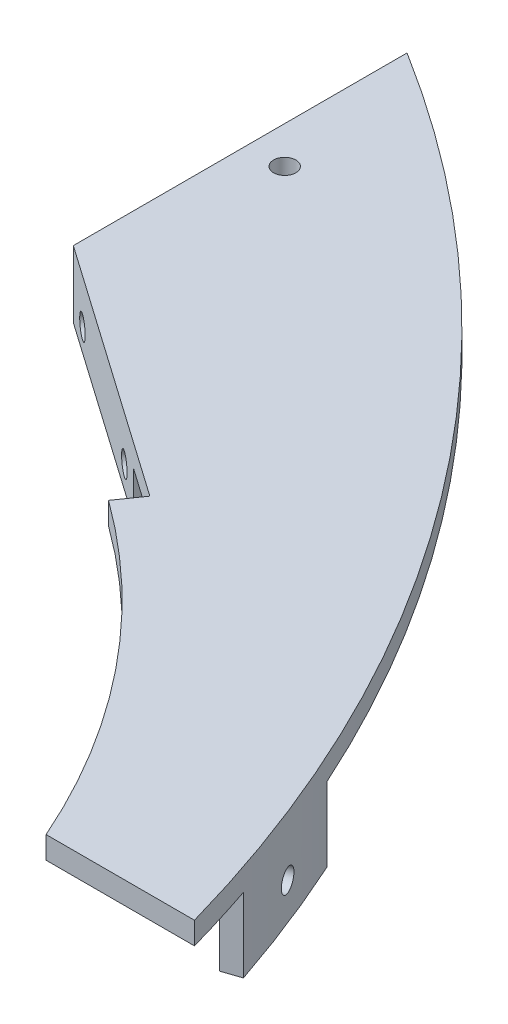
SolidWorks part; units mm, degrees
ref_plane "Front Plane" through (0, 0, 0) normal (0, 0, 1) x (1, 0, 0)
ref_plane "Top Plane" through (0, 0, 0) normal (0, 1, 0) x (1, 0, 0)
ref_plane "Right Plane" through (0, 0, 0) normal (1, 0, 0) x (0, 0, -1)
sketch "Sketch1" plane through (0, 0, 0) normal (0, 1, 0) x (1, 0, 0)
  line L0 (0, 0) -> (20, 0)
  line L1 (-67.91, 116.18) -> (-67.91, 72.58)
  arc A0 (0, 0) -> (-67.91, 72.58) centre (-137.2997, -60.4052) ccw
  arc A1 (20, 0) -> (-67.91, 116.18) centre (-172.4876, -54.3003) ccw
  dimension "D1" = 150
  dimension "D5" = 200
  dimension "D2" = 67.91
  dimension "D3" = 20
  dimension "D4" = 43.6
  dimension "D6" = 72.58
extrude "Boss-Extrude1" add sketch "Sketch1" along normal blind 3
sketch "Sketch2" plane through (0, 0, 0) normal (0, -1, 0) x (1, 0, 0)
  line L0 (-66.91, -72.0534) -> (-66.91, -70.5834) construction
  line L1 (-66.91, -70.5834) -> (-32.5056, -46.4932)
  line L2 (-67.91, -116.18) -> (-67.91, -72.58) construction
  line L3 (-66.91, -70.5834) -> (-67.91, -71.2836)
  line L4 (-67.91, -71.2836) -> (-67.91, -76.1667)
  line L5 (-32.5056, -51.3763) -> (-32.5056, -46.4932)
  line L6 (-67.91, -76.1667) -> (-32.5056, -51.3763)
  arc A0 (-67.91, -72.58) -> (0, 0) centre (-137.2997, 60.4052) ccw construction
  dimension "D5" = 4
  dimension "D1" = 1.47
  dimension "D2" = 1
  dimension "D3" = 125
  dimension "D4" = 42
extrude "Boss-Extrude2" add sketch "Sketch2" along normal blind 6
sketch "Sketch3" plane through (13.4449, 0, -19.2014) normal (0.5736, 0, -0.8192) x (-0.8192, 0, -0.5736)
  line L0 (122.2667, 3) -> (-16.383, 3) construction
  line L1 (99.3161, -6) -> (99.3161, 0) construction
  line L2 (53.2944, -6) -> (62.2961, -6)
  line L3 (99.3161, -6) -> (56.0953, -6) construction
  line L4 (62.2961, -6) -> (62.2961, 0)
  line L5 (-16.383, 0) -> (122.2667, 0) construction
  line L6 (62.2961, 0) -> (53.2944, 0)
  line L7 (53.2944, 0) -> (53.2944, -6)
  line L8 (99.3161, -6) -> (99.3161, 0)
  line L9 (99.3161, 0) -> (95.2961, 0)
  line L10 (95.2961, 0) -> (95.2961, -6)
  line L11 (95.2961, -6) -> (99.3161, -6)
  circle A0 centre (90.2961, -3) radius 1.5
  circle A1 centre (67.2961, -3) radius 1.5
  dimension "D1" = 6
  dimension "D3" = 3
  dimension "D2" = 9.02
  dimension "D4" = 23
  dimension "D5" = 5
  dimension "D6" = 5
extrude "Cut-Extrude1" cut sketch "Sketch3" against normal through all
sketch "Sketch5" plane through (0, 0, 0) normal (0, 1, 0) x (1, 0, 0)
  line L0 (-66.9113, 70.5843) -> (-67.91, 70.5843)
  line L1 (-67.91, 70.5843) -> (-67.91, 72.58)
  line L2 (-66.9113, 70.5843) -> (-32.5056, 46.4932)
  line L3 (-32.5056, 46.4932) -> (-34.7999, 43.2166)
  arc A1 (0, 0) -> (-67.91, 72.58) centre (-137.2997, -60.4052) ccw
  arc A2 (0, 0) -> (-67.91, 72.58) centre (-137.2997, -60.4052) ccw construction
  arc A3 (-34.7999, 43.2166) -> (0, 0) centre (-97.5095, -42.8995) cw
  dimension "D1" = 4
extrude "Boss-Extrude3" add sketch "Sketch5" along normal up to surface (3 mm away) up to face at (-24.6695, 3, -50.7095)
sketch "Sketch6" plane through (0, 0, 0) normal (0, -1, 0) x (1, 0, 0)
  line L0 (0, 0) -> (20, 0) construction
  line L1 (-67.91, -116.18) -> (-67.91, -70.5843) construction
  line L2 (17.3481, 0) -> (20, 0)
  line L3 (-67.91, -113.18) -> (-67.91, -116.18)
  line L4 (-60.9603, -108.6346) -> (-59.5194, -110.7397)
  line L5 (14.6278, -8.7391) -> (17.0452, -9.5535)
  line L6 (7.3961, -27.112) -> (9.7202, -28.1638)
  line L7 (-43.6009, -98.6318) -> (-45.2448, -96.6811)
  arc A0 (-67.91, -116.18) -> (20, 0) centre (-172.4876, 54.3003) ccw
  arc A1 (17.3481, 0) -> (-67.91, -113.18) centre (-172.4876, 54.3003) cw
  arc A2 (-67.91, -116.18) -> (20, 0) centre (-172.4876, 54.3003) ccw construction
  arc M11 (-67.91, -116.18) -> (20, 0) centre (-172.4876, 54.3003) ccw
  dimension "D1" = 3
  dimension "D2" = 10
  dimension "D3" = 10
  dimension "D4" = 20
  dimension "D5" = 20
extrude "Boss-Extrude4" add sketch "Sketch6" along normal blind 10 contours L7 A1 L4 M11 | L5 A1 L6 M11
sketch "Sketch7" plane through (0, -10, 0) normal (0, -1, 0) x (1, 0, 0)
  line L0 (-51.4087, -104.8848) -> (-172.4876, 54.3003) construction
  line L1 (-172.4876, 54.3003) -> (13.6155, -18.9503) construction
  arc A2 (9.7202, -28.1638) -> (17.0452, -9.5535) centre (-172.4876, 54.3003) ccw construction
  arc A3 (-59.5194, -110.7397) -> (-43.6009, -98.6318) centre (-172.4876, 54.3003) ccw construction
ref_plane "Plane1" through (-51.4087, -10, -104.8848) normal (0.6054, 0, -0.7959) x (-0.7959, 0, -0.6054)
sketch "Sketch8" plane through (-51.4087, -10, -104.8848) normal (0.6054, 0, -0.7959) x (-0.7959, 0, -0.6054)
  line L0 (10, 10) -> (-10, 0) construction
  circle A0 centre (0, 5) radius 1.5
  dimension "D1" = 3
extrude "Cut-Extrude2" cut sketch "Sketch8" against normal through all
ref_plane "Plane2" through (18.2474, 0, -7.1822) normal (0.9305, 0, -0.3663) x (-0.3663, 0, -0.9305)
sketch "Sketch9" plane through (18.2474, 0, -7.1822) normal (0.9305, 0, -0.3663) x (-0.3663, 0, -0.9305)
  line L0 (2.6468, 0) -> (22.6468, -10) construction
  line L1 (116.4255, -10) -> (12.6468, -10) construction
  line L2 (22.6468, -10) -> (22.6468, 0) construction
  circle A0 centre (12.6468, -5) radius 1.5
  dimension "D1" = 3
extrude "Cut-Extrude3" cut sketch "Sketch9" against normal through all
sketch "Sketch11" plane through (0, 0, 0) normal (0, -1, 0) x (1, 0, 0)
  line L0 (-66.91, -70.5834) -> (-66.91, -115.5625)
  line L1 (-66.91, -115.5625) -> (-66.91, -117.7489)
  line L2 (-66.91, -117.7489) -> (-78.6262, -99.1021)
  line L3 (-66.91, -70.5834) -> (-69.5392, -68.4269)
  line L4 (-69.5392, -68.4269) -> (-72.5136, -88.0424)
  arc A0 (-67.91, -116.18) -> (-59.5194, -110.7397) centre (-172.4876, 54.3003) ccw construction
  arc A1 (-78.6262, -99.1021) -> (-72.5136, -88.0424) centre (-72.5136, -95.2615) cw
extrude "Cut-Extrude5" cut sketch "Sketch11" against normal through all
sketch "Sketch10" plane through (0, 0, 0) normal (0, -1, 0) x (1, 0, 0)
  line L0 (-66.91, -93.0744) -> (-61.91, -94.0744) construction
  line L2 (-66.91, -115.5625) -> (-66.91, -70.5862) construction
  circle A0 centre (-61.91, -94.0744) radius 1.5
  dimension "D1" = 5
  dimension "3" = 3
  dimension "D2" = 1
extrude "Cut-Extrude4" cut sketch "Sketch10" against normal through all
